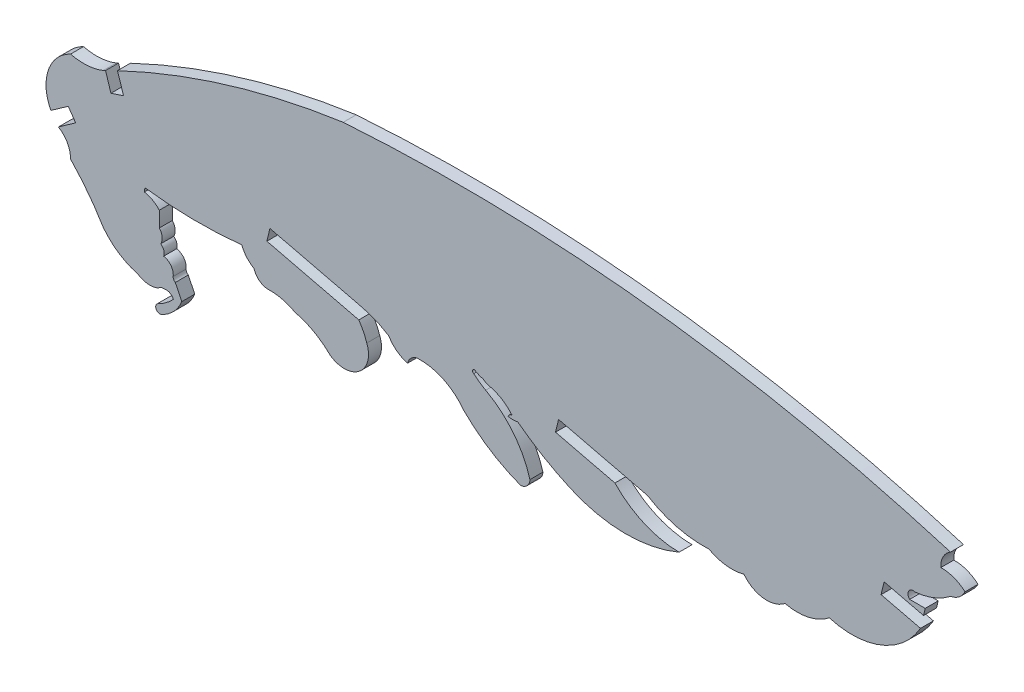
SolidWorks part; units mm, degrees
ref_plane "Front Plane" through (0, 0, 0) normal (0, 0, 1) x (1, 0, 0)
ref_plane "Top Plane" through (0, 0, 0) normal (0, 1, 0) x (1, 0, 0)
ref_plane "Right Plane" through (0, 0, 0) normal (1, 0, 0) x (0, 0, -1)
sketch "Sketch1" plane through (0, 0, 0) normal (0, 0, 1) x (1, 0, 0)
  line L0 (101.1003, 60.3743) -> (90.6566, 62.891)
  line L1 (90.6566, 62.891) -> (90.2996, 61.4094)
  line L2 (90.2996, 61.4094) -> (97.2753, 59.7284)
  line L3 (42.0539, 62.1672) -> (41.9934, 61.6984)
  line L4 (45.6278, 54.3085) -> (46.3894, 52.737)
  line L5 (133.1787, 62.891) -> (128.5487, 64.0068)
  line L6 (128.5487, 64.0068) -> (128.9057, 65.4883)
  line L7 (128.9057, 65.4883) -> (133.5357, 64.3726)
  line L8 (133.5357, 64.3726) -> (133.7362, 65.2046)
  line L9 (133.7362, 65.2046) -> (131.9097, 65.2046)
  line L10 (56.3847, 63.8841) -> (67.1875, 61.2808)
  line L11 (67.1855, 62.8489) -> (56.7418, 65.3657)
  line L12 (56.3847, 63.8841) -> (56.7418, 65.3657)
  line L13 (38.8266, 72.4578) -> (39.5509, 70.2692)
  line L14 (39.5509, 70.2692) -> (38.0602, 69.7758)
  line L15 (38.0602, 69.7758) -> (37.4314, 71.7779)
  arc A0 (133.1787, 62.891) -> (122.4688, 58.6071) centre (125.1264, 67.4924) cw
  arc A1 (122.4688, 58.6071) -> (117.2714, 57.4696) centre (118.7111, 63.3342) cw
  arc A2 (117.2714, 57.4696) -> (112.4403, 58.0196) centre (115.1269, 60.1249) cw
  arc A3 (112.4403, 58.0196) -> (108.3211, 58.5251) centre (111.0146, 63.4385) cw
  arc A4 (108.3211, 58.5251) -> (101.1003, 60.3743) centre (107.6815, 71.0499) cw
  arc A5 (97.2753, 59.7284) -> (104.8117, 56.4536) centre (104.9325, 67.041) ccw
  arc A6 (104.8117, 56.4536) -> (91.9942, 56.5931) centre (98.5625, 71.1856) cw
  arc A7 (91.9942, 56.5931) -> (85.8546, 60.2425) centre (104.9543, 85.3859) cw
  arc A8 (85.8546, 60.2425) -> (84.7353, 60.2425) centre (85.295, 62.3036) cw
  arc A9 (84.7353, 60.2425) -> (85.2, 60.5667) centre (85.1731, 60.1102) cw
  arc A10 (85.2, 60.5667) -> (82.7373, 62.1672) centre (81.4703, 57.5227) ccw
  arc A11 (82.7373, 62.1672) -> (81.8139, 62.5706) centre (82.8755, 63.7423) cw
  arc A12 (81.8139, 62.5706) -> (80.9151, 62.9302) centre (82.3531, 65.2212) cw
  arc A13 (80.9151, 62.9302) -> (80.6894, 62.5706) centre (80.7603, 62.7767) ccw
  arc A14 (80.6894, 62.5706) -> (82.0937, 61.5796) centre (85.6618, 68.1263) ccw
  arc A15 (82.0937, 61.5796) -> (87.2946, 55.082) centre (76.9403, 52.1244) cw
  arc A16 (87.2946, 55.082) -> (86.21, 53.9449) centre (86.1074, 55.1285) cw
  arc A17 (86.21, 53.9449) -> (79.5104, 58.2436) centre (92.837, 71.6429) cw
  arc A18 (79.5104, 58.2436) -> (74.0433, 60.8253) centre (74.3691, 54.4355) ccw
  arc A19 (74.0433, 60.8253) -> (72.9126, 59.732) centre (74.3389, 59.3882) ccw
  arc A20 (72.9126, 59.732) -> (70.7136, 61.4094) centre (73.8776, 63.2771) cw
  arc A21 (70.7136, 61.4094) -> (67.1855, 62.8489) centre (65.1174, 52.737) ccw
  arc A22 (37.4314, 71.7779) -> (37.1614, 71.6429) centre (78.2954, -10.301) ccw
  arc A23 (67.1875, 61.2808) -> (68.1201, 59.3882) centre (61.6606, 57.3814) cw
  arc A24 (68.1201, 59.3882) -> (63.8408, 55.9864) centre (65.4782, 58.3191) cw
  arc A25 (63.8408, 55.9864) -> (59.6659, 58.3191) centre (57.6323, 49.7772) ccw
  arc A26 (59.6659, 58.3191) -> (56.5626, 59.0578) centre (56.8077, 53.2002) ccw
  arc A27 (56.5626, 59.0578) -> (54.8765, 60.3559) centre (56.5826, 60.8279) cw
  arc A28 (54.8765, 60.3559) -> (53.4329, 62.0345) centre (56.5054, 63.2168) cw
  arc A29 (53.4329, 62.0345) -> (42.0539, 62.1672) centre (48.3096, 110.6429) cw
  arc A30 (41.9934, 61.6984) -> (43.7437, 60.715) centre (41.4646, 58.7078) cw
  arc A31 (43.7437, 60.715) -> (43.7437, 58.9073) centre (35.0707, 59.8111) cw
  arc A32 (43.7437, 58.9073) -> (43.9129, 57.3814) centre (42.812, 58.0317) cw
  arc A33 (43.9129, 57.3814) -> (44.262, 56.2972) centre (43.3952, 56.6163) cw
  arc A34 (44.262, 56.2972) -> (45.3789, 54.7899) centre (44.0301, 54.9579) cw
  arc A35 (45.3789, 54.7899) -> (45.6278, 54.3085) centre (45.8964, 54.7525) ccw
  arc A36 (46.3894, 52.737) -> (43.9129, 50.2034) centre (42.054, 54.4975) cw
  arc A37 (43.9129, 50.2034) -> (43.5273, 51.0942) centre (43.8218, 50.6928) cw
  arc A38 (43.5273, 51.0942) -> (45.4002, 52.4687) centre (40.7243, 56.8767) ccw
  arc A39 (45.4002, 52.4687) -> (44.4078, 53.0022) centre (44.5944, 52.1594) ccw
  arc A40 (44.4078, 53.0022) -> (43.6226, 52.737) centre (44.2777, 52.092) ccw
  arc A41 (43.6226, 52.737) -> (41.2333, 52.9631) centre (42.6377, 55.0675) cw
  arc A42 (41.2333, 52.9631) -> (37.1614, 55.6806) centre (43.165, 60.2669) cw
  arc A43 (37.1614, 55.6806) -> (33.3156, 60.715) centre (13.1234, 41.3036) ccw
  arc A44 (131.9097, 65.2046) -> (132.525, 66.2627) centre (132.3268, 65.67) cw
  arc A45 (132.525, 66.2627) -> (136.7079, 67.9051) centre (131.7991, 74.2592) ccw
  arc A46 (136.7079, 67.9051) -> (138.4139, 69.223) centre (136.2436, 70.2692) ccw
  arc A47 (138.4139, 69.223) -> (135.5696, 70.2692) centre (135.6852, 66.1939) ccw
  arc A48 (135.5696, 70.2692) -> (136.7079, 72.4169) centre (137.8897, 70.4149) cw
  arc A49 (136.7079, 72.4169) -> (65.3531, 80.4697) centre (78.9983, -118.7815) ccw
  arc A50 (65.3531, 80.4697) -> (38.8266, 72.4578) centre (78.2954, -10.301) ccw
  arc A51 (37.1614, 71.6429) -> (33.3156, 71.3923) centre (34.8525, 77.4407) cw
  arc A52 (33.3156, 71.3923) -> (31.9683, 63.2168) centre (35.474, 66.8379) ccw
  arc A53 (33.3156, 60.715) -> (31.9683, 63.2168) centre (30.3972, 60.757) ccw
extrude "Boss-Extrude1" add sketch "Sketch1" along normal blind 1.524
sketch "Sketch2" plane through (0, 0, 1.524) normal (0, 0, 1) x (1, 0, 0)
  line L1 (31.4086, 63.8571) -> (33.486, 65.3187) construction
  line L2 (31.8471, 63.2339) -> (33.9245, 64.6955)
  line L3 (30.9702, 64.4803) -> (33.0475, 65.9419)
  line L4 (31.8471, 63.2339) -> (30.9702, 64.4803)
  line L5 (33.9245, 64.6955) -> (33.0475, 65.9419)
  dimension "D1" = 0.762
  dimension "D2" = 0.762
extrude "Cut-Extrude1" cut sketch "Sketch2" against normal blind 1.524
ref_plane "Plane1" through (33.3156, 71.3923, 1.524) normal (-0.9037, -0.4282, 0) x (0, 0, 1)
